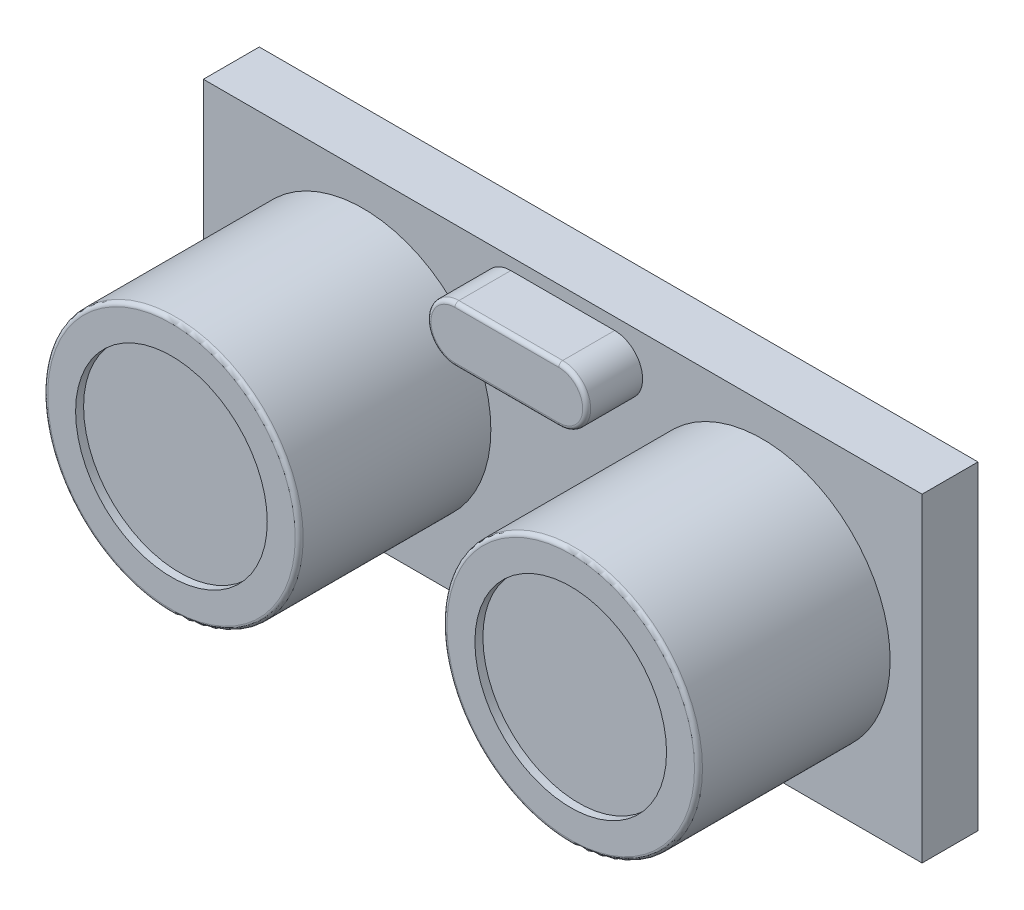
SolidWorks part; units mm, degrees
ref_plane "Front Plane" through (0, 0, 0) normal (0, 0, 1) x (1, 0, 0)
ref_plane "Top Plane" through (0, 0, 0) normal (0, 1, 0) x (1, 0, 0)
ref_plane "Right Plane" through (0, 0, 0) normal (1, 0, 0) x (0, 0, -1)
sketch "Sketch1" plane through (0, 0, 0) normal (0, 0, 1) x (1, 0, 0)
  line L1 (-22.5, 10) -> (22.5, 10)
  line L2 (-22.5, 10) -> (-22.5, -10)
  line L3 (-22.5, -10) -> (22.5, -10)
  line L4 (22.5, 10) -> (22.5, -10)
  line L5 (-22.5, 10) -> (22.5, -10) construction
  line L6 (-22.5, -10) -> (22.5, 10) construction
  point P0 (0, 0)
  dimension "D1" = 20
  dimension "D2" = 45
extrude "Boss-Extrude1" add sketch "Sketch1" along normal blind 3.5
sketch "Sketch2" plane through (0, 0, 3.5) normal (0, 0, 1) x (1, 0, 0)
  line L0 (-22.5, -10) -> (22.5, -10) construction
  line L1 (-22.5, 10) -> (-12.5, 10) construction
  line L2 (-22.5, 10) -> (-22.5, -10) construction
  line L3 (-22.5, -10) -> (-12.5, -10) construction
  line L4 (-12.5, 10) -> (-12.5, -10) construction
  line L6 (22.5, 10) -> (12.5, 10) construction
  line L7 (22.5, 10) -> (22.5, -10) construction
  line L8 (22.5, -10) -> (12.5, -10) construction
  line L9 (12.5, 10) -> (12.5, -10) construction
  circle A0 centre (12.5, 0) radius 8
  circle A1 centre (-12.5, 0) radius 8
  point P16 (0, 0)
  point P17 (-12.5, 0)
  point P18 (0, 0)
  point P19 (12.5, 0)
  point P20 (-21.4742, 0)
  point P21 (-21.4742, 0)
  dimension "D1" = 16
  dimension "D2" = 10
extrude "Boss-Extrude2" add sketch "Sketch2" along normal blind 12
sketch "Sketch3" plane through (0, 0, 15.5) normal (0, 0, 1) x (1, 0, 0)
  circle A0 centre (-12.5, 0) radius 6
  circle A1 centre (12.5, 0) radius 6
  circle A2 centre (12.5, 0) radius 8 construction
  circle A3 centre (-12.5, 0) radius 8 construction
  dimension "D1" = 2
extrude "Cut-Extrude1" cut sketch "Sketch3" against normal blind 0.5
fillet "Fillet1" radius 0.25 2 edges at (20.5, 0, 15.5) (-4.5, 0, 15.5)
sketch "Sketch4" plane through (0, 0, 3.5) normal (0, 0, 1) x (1, 0, 0)
  line L0 (-3.25, 7.5) -> (3.25, 7.5) construction
  line L1 (-3.25, 9.25) -> (3.25, 9.25)
  line L2 (-3.25, 5.75) -> (3.25, 5.75)
  line L3 (22.5, 10) -> (-22.5, 10) construction
  arc A0 (-3.25, 9.25) -> (-3.25, 5.75) centre (-3.25, 7.5) ccw
  arc A1 (3.25, 5.75) -> (3.25, 9.25) centre (3.25, 7.5) ccw
  point P2 (0, 7.5)
  point P9 (0, 0)
  dimension "D1" = 3.5
  dimension "D2" = 6.5
  dimension "D3" = 2.5
extrude "Boss-Extrude3" add sketch "Sketch4" along normal blind 3.5
fillet "Fillet2" radius 0.25 4 edges at (0, 9.25, 7) (5, 7.5, 7) (0, 5.75, 7) (-5, 7.5, 7)
